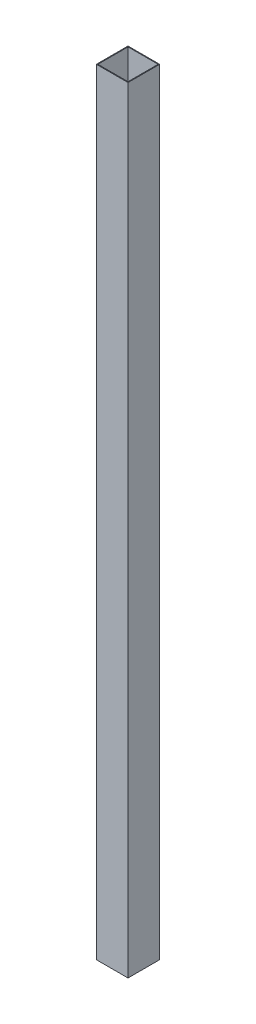
SolidWorks part; units mm, degrees
ref_plane "Front Plane" through (0, 0, 0) normal (0, 0, 1) x (1, 0, 0)
ref_plane "Top Plane" through (0, 0, 0) normal (0, 1, 0) x (1, 0, 0)
ref_plane "Right Plane" through (0, 0, 0) normal (1, 0, 0) x (0, 0, -1)
sketch "Sketch2" plane through (0, 0, 0) normal (0, 1, 0) x (1, 0, 0)
  line L1 (0, 0) -> (25.4, 0)
  line L2 (0, 0) -> (0, 25.4)
  line L3 (0, 25.4) -> (25.4, 25.4)
  line L4 (25.4, 0) -> (25.4, 25.4)
  dimension "D1" = 25.4
  dimension "D2" = 25.4
extrude "Extrude-Thin1" add sketch "Sketch2" along normal blind 622.3 thin thin type one direction reverse wall 0.6
